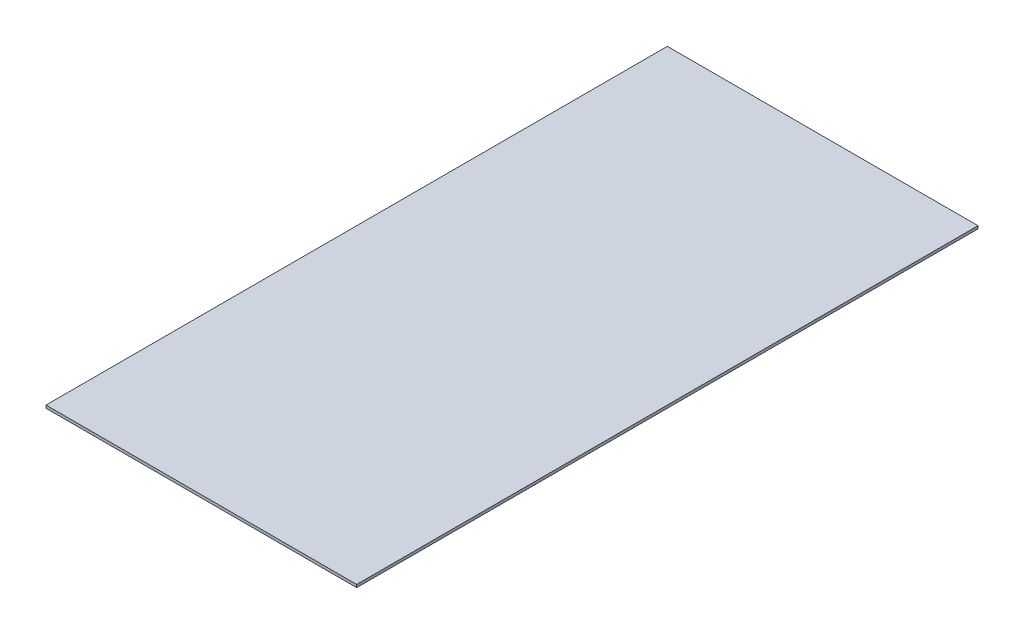
SolidWorks part; units mm, degrees
ref_plane "Front Plane" through (0, 0, 0) normal (0, 0, 1) x (1, 0, 0)
ref_plane "Top Plane" through (0, 0, 0) normal (0, 1, 0) x (1, 0, 0)
ref_plane "Right Plane" through (0, 0, 0) normal (1, 0, 0) x (0, 0, -1)
sketch "Sketch1" plane through (0, 0, 0) normal (0, 1, 0) x (1, 0, 0)
  line L1 (-610, 1220) -> (610, 1220)
  line L2 (-610, 1220) -> (-610, -1220)
  line L3 (-610, -1220) -> (610, -1220)
  line L4 (610, 1220) -> (610, -1220)
  line L5 (-610, 1220) -> (610, -1220) construction
  line L6 (-610, -1220) -> (610, 1220) construction
  point P0 (0, 0)
  dimension "D1" = 1220
  dimension "D2" = 2440
extrude "Boss-Extrude1" add sketch "Sketch1" along normal blind 11 contours L2 L1 L4 L3
